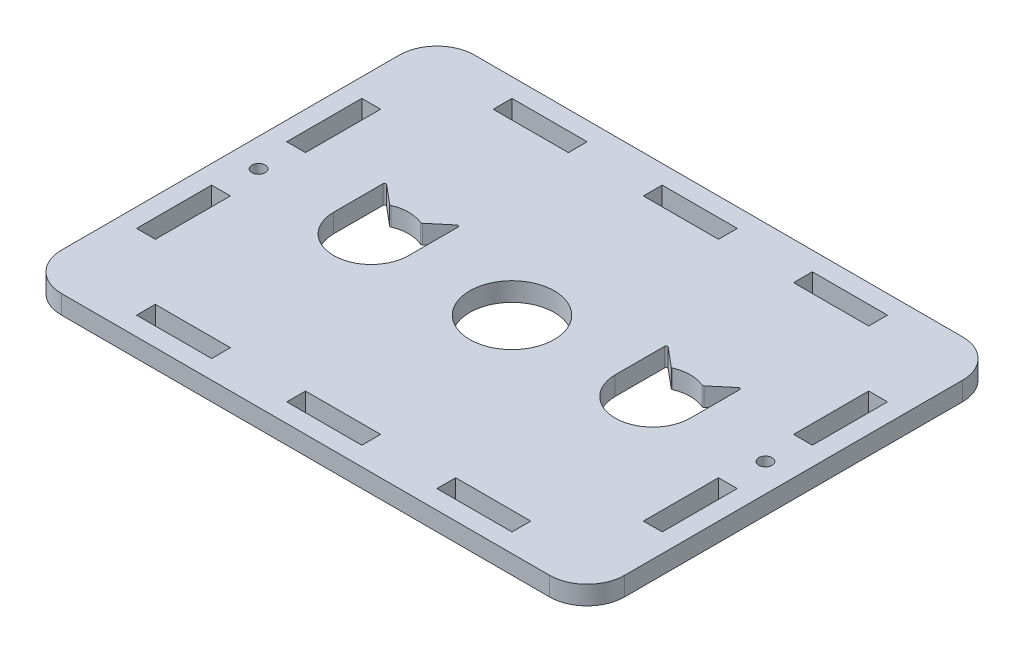
SolidWorks part; units mm, degrees
ref_plane "Front Plane" through (0, 0, 0) normal (0, 0, 1) x (1, 0, 0)
ref_plane "Top Plane" through (0, 0, 0) normal (0, 1, 0) x (1, 0, 0)
ref_plane "Right Plane" through (0, 0, 0) normal (1, 0, 0) x (0, 0, -1)
sketch "Sketch1" plane through (0, 0, 0) normal (0, 1, 0) x (1, 0, 0)
  line L1 (0, 0) -> (190.5, 0)
  line L2 (0, 0) -> (0, 139.7)
  line L3 (0, 139.7) -> (190.5, 139.7)
  line L4 (190.5, 0) -> (190.5, 139.7)
  dimension "D1" = 139.7
  dimension "D2" = 190.5
extrude "Boss-Extrude1" add sketch "Sketch1" along normal blind 6.35
sketch "Sketch13" plane through (0, 6.35, 0) normal (0, 1, 0) x (1, 0, 0)
  line L1 (0, 139.7) -> (0, 0) construction
  line L2 (31.75, 12.7) -> (57.15, 12.7)
  line L3 (31.75, 12.7) -> (31.75, 6.35)
  line L4 (31.75, 6.35) -> (57.15, 6.35)
  line L5 (57.15, 12.7) -> (57.15, 6.35)
  line L6 (31.75, 12.7) -> (57.15, 6.35) construction
  line L7 (31.75, 6.35) -> (57.15, 12.7) construction
  line L8 (0, 0) -> (190.5, 0) construction
  line L9 (82.55, 12.7) -> (107.95, 12.7)
  line L10 (82.55, 12.7) -> (82.55, 6.35)
  line L11 (82.55, 6.35) -> (107.95, 6.35)
  line L12 (107.95, 12.7) -> (107.95, 6.35)
  line L13 (133.35, 12.7) -> (158.75, 12.7)
  line L14 (133.35, 12.7) -> (133.35, 6.35)
  line L15 (133.35, 6.35) -> (158.75, 6.35)
  line L16 (158.75, 12.7) -> (158.75, 6.35)
  point P0 (44.45, 9.525)
  dimension "D1" = 31.75
  dimension "D2" = 6.35
  dimension "D4" = 6.35
  dimension "D5" = 3
  dimension "D3" = 25.4
extrude "Cut-Extrude6" cut sketch "Sketch13" against normal blind 6.35
pattern_linear "LPattern7" count 2 spacing 120.65 along (0, 0, -1) of "Cut-Extrude6"
sketch "Sketch14" plane through (0, 6.35, 0) normal (0, 1, 0) x (1, 0, 0)
  line L0 (0, 139.7) -> (0, 0) construction
  line L1 (6.35, 31.75) -> (12.7, 31.75)
  line L2 (6.35, 31.75) -> (6.35, 57.15)
  line L3 (6.35, 57.15) -> (12.7, 57.15)
  line L4 (12.7, 31.75) -> (12.7, 57.15)
  line L5 (0, 0) -> (190.5, 0) construction
  line L6 (177.8, 57.15) -> (184.15, 57.15)
  line L7 (177.8, 31.75) -> (177.8, 57.15)
  line L8 (184.15, 31.75) -> (184.15, 57.15)
  line L9 (177.8, 31.75) -> (184.15, 31.75)
  line L10 (177.8, 107.95) -> (184.15, 107.95)
  line L11 (177.8, 82.55) -> (177.8, 107.95)
  line L12 (184.15, 82.55) -> (184.15, 107.95)
  line L13 (177.8, 82.55) -> (184.15, 82.55)
  line L14 (6.35, 107.95) -> (12.7, 107.95)
  line L15 (6.35, 82.55) -> (6.35, 107.95)
  line L16 (12.7, 82.55) -> (12.7, 107.95)
  line L17 (6.35, 82.55) -> (12.7, 82.55)
  dimension "D1" = 25.4
  dimension "D2" = 6.35
  dimension "D3" = 6.35
  dimension "D4" = 31.75
  dimension "D5" = 2
  dimension "D6" = 2
extrude "Cut-Extrude7" cut sketch "Sketch14" against normal blind 6.35
hole_wizard "#8 Clearance Hole1" positions "Sketch16" profile "Sketch15" hole size "#8" standard "ANSI Inch"
sketch "Sketch16" plane through (0, 6.35, 0) normal (0, 1, 0) x (1, 0, 0)
  line L0 (12.7, 57.15) -> (6.35, 57.15) construction
  line L1 (6.35, 57.15) -> (6.35, 31.75) construction
  line L2 (184.15, 57.15) -> (177.8, 57.15) construction
  line L3 (177.8, 57.15) -> (177.8, 31.75) construction
  point P0 (9.525, 69.85)
  point P3 (9.525, 57.15)
  point P8 (180.975, 69.85)
  dimension "D1" = 12.7
  dimension "D2" = 3.175
  dimension "D3" = 12.7
  dimension "D4" = 3.175
sketch "Sketch15" plane through (9.525, 6.35, -69.85) normal (1, 0, 0) x (0, 0, 1)
  line L0 (0, 0) -> (0, 11.5107)
  line L1 (0, 11.5107) -> (2.2479, 10.16)
  line L2 (2.2479, 10.16) -> (2.2479, 0)
  line L5 (2.2479, 0) -> (0, 0)
  line L10 (0, 11.5107) -> (-2.2479, 10.16) construction
  line L11 (0, -6.35) -> (0, 107.95) construction
  dimension "Hole Dia." = 4.4958
  dimension "Hole Depth" = 10.16
  dimension "Drill Angle" = 118
sketch "Sketch18" plane through (0, 6.35, 0) normal (0, 1, 0) x (1, 0, 0)
  line L0 (0, 139.7) -> (0, 0) construction
  circle A0 centre (95.25, 69.85) radius 14.2875
  circle A2 centre (9.525, 69.85) radius 2.2479 construction
  dimension "D1" = 28.575
  dimension "D2" = 95.25
  dimension "D3" = 0
extrude "Cut-Extrude9" cut sketch "Sketch18" against normal blind 7.62
sketch "Sketch19" plane through (0, 6.35, 0) normal (0, 1, 0) x (1, 0, 0)
  line L0 (12.7, 82.55) -> (177.8, 82.55)
  line L3 (12.7, 107.95) -> (6.35, 107.95) construction
  dimension "D1" = 25.4
sketch "Sketch20" plane through (0, 6.35, 0) normal (0, 1, 0) x (1, 0, 0)
  text T0 "Countercat" font "DS-Digital" height in points 72
extrude "Cut-Extrude10" [suppressed] cut sketch "Sketch20" against normal blind 10.16
sketch "Sketch21" plane through (0, 6.35, 0) normal (0, 1, 0) x (1, 0, 0)
  line L0 (12.7, 69.85) -> (63.5, 69.85)
  line L2 (177.8, 69.85) -> (127, 69.85)
  circle A0 centre (95.25, 69.85) radius 14.2875 construction
  dimension "D1" = 50.8
  dimension "D2" = 50.8
  dimension "D3" = 0
  dimension "D4" = 0
sketch "Sketch22" plane through (0, 6.35, 0) normal (0, 1, 0) x (1, 0, 0)
  text T0 "armed" font "DS-Digital" height in points 36
  text T1 "Safe" font "DS-Digital" height in points 36
extrude "Cut-Extrude11" [suppressed] cut sketch "Sketch22" against normal blind 10.16
sketch "Sketch24" plane through (0, 6.35, 0) normal (0, 1, 0) x (1, 0, 0)
  line L0 (6.35, 82.55) -> (12.7, 82.55) construction
  line L2 (34.925, 87.63) -> (34.925, 69.85)
  line L4 (42.3477, 81.4016) -> (34.925, 87.63)
  line L7 (60.325, 87.63) -> (60.325, 69.85)
  line L8 (52.9023, 81.4016) -> (60.325, 87.63)
  arc A0 (52.9023, 81.4016) -> (42.3477, 81.4016) centre (47.625, 69.85) ccw
  arc A1 (34.925, 69.85) -> (60.325, 69.85) centre (47.625, 69.85) ccw
  circle A2 centre (9.525, 69.85) radius 2.2479 construction
  arc A7 (42.3477, 81.4016) -> (40.005, 80.01) centre (47.625, 69.85) ccw
  arc A8 (34.925, 69.85) -> (35.8545, 74.6191) centre (47.625, 69.85) cw
  arc A9 (52.9023, 81.4016) -> (55.245, 80.01) centre (47.625, 69.85) cw
  arc A10 (60.325, 69.85) -> (59.3955, 74.6191) centre (47.625, 69.85) ccw
  point P1 (9.525, 82.55)
  dimension "D1" = 25.4
  dimension "D2" = 12.7
  dimension "D3" = 38.1
  dimension "D4" = 50
extrude "Cut-Extrude16" cut sketch "Sketch24" against normal blind 6.35
fillet "Fillet2" radius 0.508 4 edges at (60.325, 3.175, -87.63) (52.9023, 3.175, -81.4016) (42.3477, 3.175, -81.4016) (34.925, 3.175, -87.63)
sketch "Sketch25" plane through (0, 6.35, 0) normal (0, 1, 0) x (1, 0, 0)
  line L0 (177.8, 82.55) -> (184.15, 82.55) construction
  line L2 (130.175, 87.63) -> (130.175, 69.85)
  line L4 (137.5977, 81.4016) -> (130.175, 87.63)
  line L7 (155.575, 87.63) -> (155.575, 69.85)
  line L8 (148.1523, 81.4016) -> (155.575, 87.63)
  arc A0 (148.1523, 81.4016) -> (137.5977, 81.4016) centre (142.875, 69.85) ccw
  arc A1 (130.175, 69.85) -> (155.575, 69.85) centre (142.875, 69.85) ccw
  circle A2 centre (180.975, 69.85) radius 2.2479 construction
  arc A7 (137.5977, 81.4016) -> (135.255, 80.01) centre (142.875, 69.85) ccw
  arc A8 (130.175, 69.85) -> (130.1902, 69.2281) centre (142.875, 69.85) cw
  arc A9 (148.1523, 81.4016) -> (150.495, 80.01) centre (142.875, 69.85) cw
  arc A10 (155.575, 69.85) -> (155.5598, 69.2281) centre (142.875, 69.85) ccw
  point P3 (180.975, 82.55)
  dimension "D1" = 25.4
  dimension "D2" = 38.1
  dimension "D3" = 12.7
  dimension "D19" = 5.08
  dimension "D4" = 50
  dimension "D5" = 17.78
extrude "Cut-Extrude17" cut sketch "Sketch25" against normal blind 6.35 contours A8 A1 A0 A7 | L2 A8 A7 L4 | L8 A8 L7
fillet "Fillet5" radius 0.508 4 edges at (137.5977, 3.175, -81.4016) (130.175, 3.175, -87.63) (155.575, 3.175, -87.63) (148.1523, 3.175, -81.4016)
fillet "Fillet6" radius 12.7 4 edges at (190.5, 3.175, -139.7) (190.5, 3.175, 0) (0, 3.175, 0) (0, 3.175, -139.7)
equation "\"THICK\"= .25"
